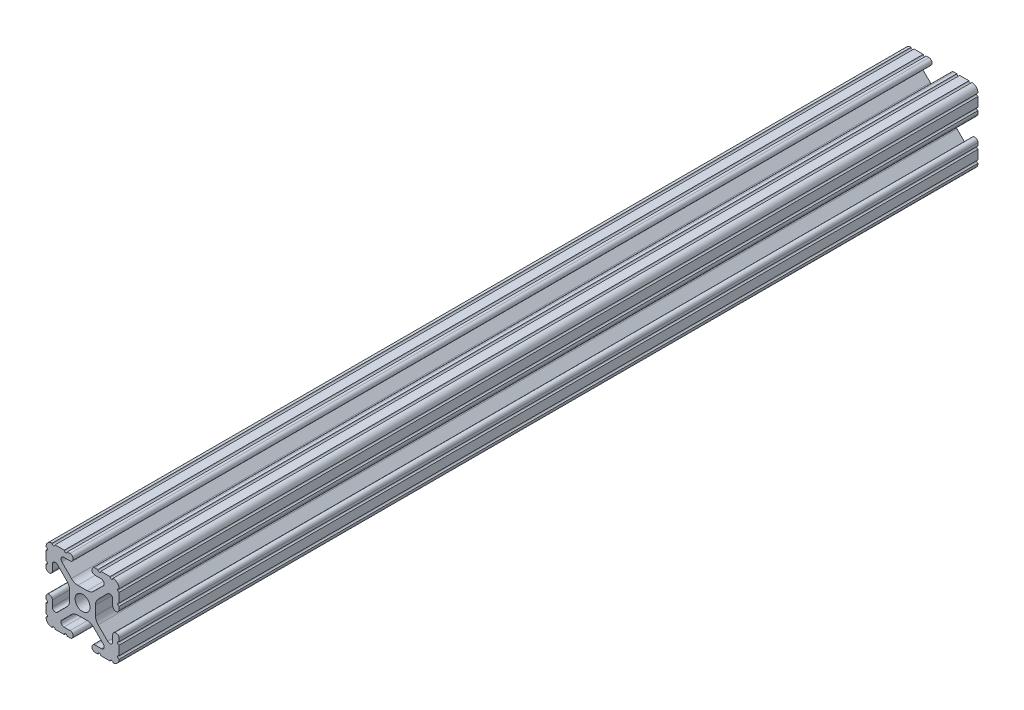
SolidWorks part; units mm, degrees
ref_plane "Front Plane" through (0, 0, 0) normal (0, 0, 1) x (1, 0, 0)
ref_plane "Top Plane" through (0, 0, 0) normal (0, 1, 0) x (1, 0, 0)
ref_plane "Right Plane" through (0, 0, 0) normal (1, 0, 0) x (0, 0, -1)
ref_plane "Plane1" through (0, 0, -25.4) normal (0, 0, -1) x (-1, 0, 0)
sketch "Sketch1" plane through (0, 0, -25.4) normal (0, 0, -1) x (-1, 0, 0)
  line L0 (12.7, -9.5504) -> (12.7, -6.3331)
  line L1 (12.7, -5.3171) -> (12.7, -4.3434)
  line L2 (10.4902, -4.3434) -> (10.4902, -6.4748)
  line L3 (8.7558, -7.1932) -> (5.4257, -3.8632)
  line L4 (4.4958, -1.6181) -> (4.4958, 1.6181)
  line L5 (5.4257, 3.8632) -> (8.7558, 7.1932)
  line L6 (10.4902, 6.4748) -> (10.4902, 4.3434)
  line L7 (12.7, 4.3434) -> (12.7, 5.3171)
  line L8 (12.7, 6.3331) -> (12.7, 9.5504)
  line L9 (9.5504, 12.7) -> (6.3331, 12.7)
  line L10 (5.3171, 12.7) -> (4.3434, 12.7)
  line L11 (4.3434, 10.4902) -> (6.4748, 10.4902)
  line L12 (7.1932, 8.7558) -> (3.8632, 5.4257)
  line L13 (1.6181, 4.4958) -> (-1.6181, 4.4958)
  line L14 (-3.8632, 5.4257) -> (-7.1932, 8.7558)
  line L15 (-6.4748, 10.4902) -> (-4.3434, 10.4902)
  line L16 (-4.3434, 12.7) -> (-5.3171, 12.7)
  line L17 (-6.3331, 12.7) -> (-9.5504, 12.7)
  line L18 (-12.7, 9.5504) -> (-12.7, 6.3331)
  line L19 (-12.7, 5.3171) -> (-12.7, 4.3434)
  line L20 (-10.4902, 4.3434) -> (-10.4902, 6.4748)
  line L21 (-8.7558, 7.1932) -> (-5.4257, 3.8632)
  line L22 (-4.4958, 1.6181) -> (-4.4958, -1.6181)
  line L23 (-5.4257, -3.8632) -> (-8.7558, -7.1932)
  line L24 (-10.4902, -6.4748) -> (-10.4902, -4.3434)
  line L25 (-12.7, -4.3434) -> (-12.7, -5.3171)
  line L26 (-12.7, -6.3331) -> (-12.7, -9.5504)
  line L27 (-9.5504, -12.7) -> (-6.3331, -12.7)
  line L28 (-5.3171, -12.7) -> (-4.3434, -12.7)
  line L29 (-4.3434, -10.4902) -> (-6.4748, -10.4902)
  line L30 (-7.1932, -8.7558) -> (-3.8632, -5.4257)
  line L31 (-1.6181, -4.4958) -> (1.6181, -4.4958)
  line L32 (3.8632, -5.4257) -> (7.1932, -8.7558)
  line L33 (6.4748, -10.4902) -> (4.3434, -10.4902)
  line L34 (4.3434, -12.7) -> (5.3171, -12.7)
  line L35 (6.3331, -12.7) -> (9.5504, -12.7)
  arc A0 (12.6998, -10.5664) -> (12.7, -9.5504) centre (12.7, -10.0584) cw
  arc A1 (12.7, -6.3331) -> (12.7, -5.3171) centre (12.7, -5.8251) cw
  arc A2 (12.7, -4.3434) -> (10.4902, -4.3434) centre (11.5951, -4.3434) ccw
  arc A3 (10.4902, -6.4748) -> (8.7558, -7.1932) centre (9.4742, -6.4748) cw
  arc A4 (5.4257, -3.8632) -> (4.4958, -1.6181) centre (7.6708, -1.6181) cw
  arc A5 (4.4958, 1.6181) -> (5.4257, 3.8632) centre (7.6708, 1.6181) cw
  arc A6 (8.7558, 7.1932) -> (10.4902, 6.4748) centre (9.4742, 6.4748) cw
  arc A7 (10.4902, 4.3434) -> (12.7, 4.3434) centre (11.5951, 4.3434) ccw
  arc A8 (12.7, 5.3171) -> (12.7, 6.3331) centre (12.7, 5.8251) cw
  arc A9 (12.7, 9.5504) -> (12.6998, 10.5664) centre (12.7, 10.0584) cw
  arc A10 (12.6998, 10.5664) -> (10.5664, 12.6998) centre (10.5918, 10.5918) ccw
  arc A11 (10.5664, 12.6998) -> (9.5504, 12.7) centre (10.0584, 12.7) cw
  arc A12 (6.3331, 12.7) -> (5.3171, 12.7) centre (5.8251, 12.7) cw
  arc A13 (4.3434, 12.7) -> (4.3434, 10.4902) centre (4.3434, 11.5951) ccw
  arc A14 (6.4748, 10.4902) -> (7.1932, 8.7558) centre (6.4748, 9.4742) cw
  arc A15 (3.8632, 5.4257) -> (1.6181, 4.4958) centre (1.6181, 7.6708) cw
  arc A16 (-1.6181, 4.4958) -> (-3.8632, 5.4257) centre (-1.6181, 7.6708) cw
  arc A17 (-7.1932, 8.7558) -> (-6.4748, 10.4902) centre (-6.4748, 9.4742) cw
  arc A18 (-4.3434, 10.4902) -> (-4.3434, 12.7) centre (-4.3434, 11.5951) ccw
  arc A19 (-5.3171, 12.7) -> (-6.3331, 12.7) centre (-5.8251, 12.7) cw
  arc A20 (-9.5504, 12.7) -> (-10.5664, 12.6998) centre (-10.0584, 12.7) cw
  arc A21 (-10.5664, 12.6998) -> (-12.6998, 10.5664) centre (-10.5918, 10.5918) ccw
  arc A22 (-12.6998, 10.5664) -> (-12.7, 9.5504) centre (-12.7, 10.0584) cw
  arc A23 (-12.7, 6.3331) -> (-12.7, 5.3171) centre (-12.7, 5.8251) cw
  arc A24 (-12.7, 4.3434) -> (-10.4902, 4.3434) centre (-11.5951, 4.3434) ccw
  arc A25 (-10.4902, 6.4748) -> (-8.7558, 7.1932) centre (-9.4742, 6.4748) cw
  arc A26 (-5.4257, 3.8632) -> (-4.4958, 1.6181) centre (-7.6708, 1.6181) cw
  arc A27 (-4.4958, -1.6181) -> (-5.4257, -3.8632) centre (-7.6708, -1.6181) cw
  arc A28 (-8.7558, -7.1932) -> (-10.4902, -6.4748) centre (-9.4742, -6.4748) cw
  arc A29 (-10.4902, -4.3434) -> (-12.7, -4.3434) centre (-11.5951, -4.3434) ccw
  arc A30 (-12.7, -5.3171) -> (-12.7, -6.3331) centre (-12.7, -5.8251) cw
  arc A31 (-12.7, -9.5504) -> (-12.6998, -10.5664) centre (-12.7, -10.0584) cw
  arc A32 (-12.6998, -10.5664) -> (-10.5664, -12.6998) centre (-10.5918, -10.5918) ccw
  arc A33 (-10.5664, -12.6998) -> (-9.5504, -12.7) centre (-10.0584, -12.7) cw
  arc A34 (-6.3331, -12.7) -> (-5.3171, -12.7) centre (-5.8251, -12.7) cw
  arc A35 (-4.3434, -12.7) -> (-4.3434, -10.4902) centre (-4.3434, -11.5951) ccw
  arc A36 (-6.4748, -10.4902) -> (-7.1932, -8.7558) centre (-6.4748, -9.4742) cw
  arc A37 (-3.8632, -5.4257) -> (-1.6181, -4.4958) centre (-1.6181, -7.6708) cw
  arc A38 (1.6181, -4.4958) -> (3.8632, -5.4257) centre (1.6181, -7.6708) cw
  arc A39 (7.1932, -8.7558) -> (6.4748, -10.4902) centre (6.4748, -9.4742) cw
  arc A40 (4.3434, -10.4902) -> (4.3434, -12.7) centre (4.3434, -11.5951) ccw
  arc A41 (5.3171, -12.7) -> (6.3331, -12.7) centre (5.8251, -12.7) cw
  arc A42 (9.5504, -12.7) -> (10.5664, -12.6998) centre (10.0584, -12.7) cw
  arc A43 (10.5664, -12.6998) -> (12.6998, -10.5664) centre (10.5918, -10.5918) ccw
  circle A44 centre (0, 0) radius 2.6035
extrude "Boss-Extrude1" add sketch "Sketch1" against normal blind 298.45
